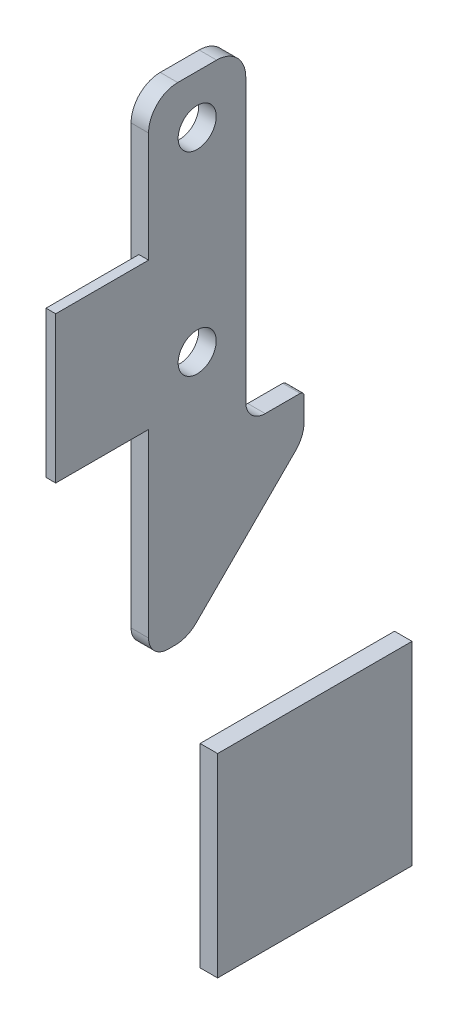
SolidWorks part; units mm, degrees
material "6061-T6 (SS)"
ref_plane "Front Plane" through (0, 0, 0) normal (0, 0, 1) x (1, 0, 0)
ref_plane "Top Plane" through (0, 0, 0) normal (0, 1, 0) x (1, 0, 0)
ref_plane "Right Plane" through (0, 0, 0) normal (1, 0, 0) x (0, 0, -1)
sketch "Sketch1" plane through (0, 0, 0) normal (1, 0, 0) x (0, 0, -1)
  line L0 (-6.35, -57.15) -> (-6.35, 6.35)
  line L1 (-6.35, 6.35) -> (6.35, 6.35)
  line L2 (6.35, 6.35) -> (6.35, -36.83)
  line L3 (6.35, -36.83) -> (13.97, -36.83)
  line L4 (13.97, -36.83) -> (13.97, -41.91)
  line L5 (13.97, -41.91) -> (-1.27, -57.15)
  line L6 (-1.27, -57.15) -> (-6.35, -57.15)
  line L7 (0, 0) -> (0, 6.35) construction
  circle A0 centre (0, 0) radius 2.4892
  circle A1 centre (0, -25.4) radius 2.4892
  dimension "D2" = 4.9784
  dimension "D1" = 12.7
  dimension "D3" = 25.4
  dimension "D4" = 6.35
  dimension "D5" = 36.83
  dimension "D6" = 13.97
  dimension "D7" = 5.08
  dimension "D8" = 45
  dimension "D9" = 5.08
extrude "Boss-Extrude1" add sketch "Sketch1" along normal mid plane 2.286
fillet "Fillet1" radius 2.54 1 edges at (0, -36.83, -6.35)
fillet "Fillet2" radius 0.508 1 edges at (0, -36.83, -13.97)
fillet "Fillet3" radius 3.81 4 edges at (0, -57.15, 1.27) (0, -41.91, -13.97) (0, 6.35, -6.35) (0, 6.35, 6.35)
fillet "Fillet4" radius 2.54 1 edges at (0, -57.15, 6.35)
sketch "Sketch2" [suppressed] plane through (1.143, 0, 0) normal (1, 0, 0) x (0, 0, -1)
  line L1 (-42.8157, -56.6441) -> (-58.1996, -56.6441)
  line L2 (-42.8157, -56.6441) -> (-42.8157, -42.612)
  line L3 (-42.8157, -42.612) -> (-58.1996, -42.612)
  line L4 (-58.1996, -56.6441) -> (-58.1996, -42.612)
  line L5 (-42.8157, -56.6441) -> (-58.1996, -42.612) construction
  line L6 (-42.8157, -42.612) -> (-58.1996, -56.6441) construction
  point P4 (-50.5076, -49.6281)
extrude "Boss-Extrude2" [suppressed] add sketch "Sketch2" against normal up to surface (2.286 mm away) separate body
sketch "Sketch3" [suppressed] plane through (-1.143, 0, 0) normal (-1, 0, 0) x (0, 0, 1)
  line L0 (6.35, -52.8635) -> (6.35, -37.6235)
  line L1 (6.35, -52.8635) -> (10.804, -52.8635)
  line L2 (6.35, -37.6235) -> (10.804, -37.6235)
  line L3 (10.804, -52.8635) -> (10.804, -37.6235)
  line L4 (6.35, 2.54) -> (6.35, -54.61) construction
  line L5 (-6.35, 1.9886) -> (-6.35, -13.2514)
  line L6 (-6.35, 1.9886) -> (-12.0659, 1.9886)
  line L7 (-6.35, -13.2514) -> (-12.0659, -13.2514)
  line L8 (-12.0659, 1.9886) -> (-12.0659, -13.2514)
  line L9 (-6.35, -34.29) -> (-6.35, 2.54) construction
  dimension "D1" = 15.24
extrude "Boss-Extrude3" [suppressed] add sketch "Sketch3" against normal blind 1.27
sketch "Sketch4" plane through (1.143, 0, 0) normal (1, 0, 0) x (0, 0, -1)
  line L1 (2.6721, -72.1928) -> (28.0721, -72.1928)
  line L2 (2.6721, -72.1928) -> (2.6721, -97.5928)
  line L3 (2.6721, -97.5928) -> (28.0721, -97.5928)
  line L4 (28.0721, -72.1928) -> (28.0721, -97.5928)
  dimension "D1" = 25.4
  dimension "D2" = 25.4
extrude "Boss-Extrude4" add sketch "Sketch4" against normal up to surface (2.286 mm away) separate body up to face at (-1.143, 0, -2.4892)
sketch "Sketch5" plane through (1.143, 0, 0) normal (1, 0, 0) x (0, 0, -1)
  line L0 (-6.35, 2.54) -> (-6.35, -54.61) construction
  line L1 (-6.35, -31.0059) -> (-18.4832, -31.0059)
  line L2 (-6.35, -31.0059) -> (-6.35, -11.8471)
  line L3 (-6.35, -11.8471) -> (-18.4832, -11.8471)
  line L4 (-18.4832, -31.0059) -> (-18.4832, -11.8471)
extrude "Boss-Extrude5" add sketch "Sketch5" against normal blind 1.27
